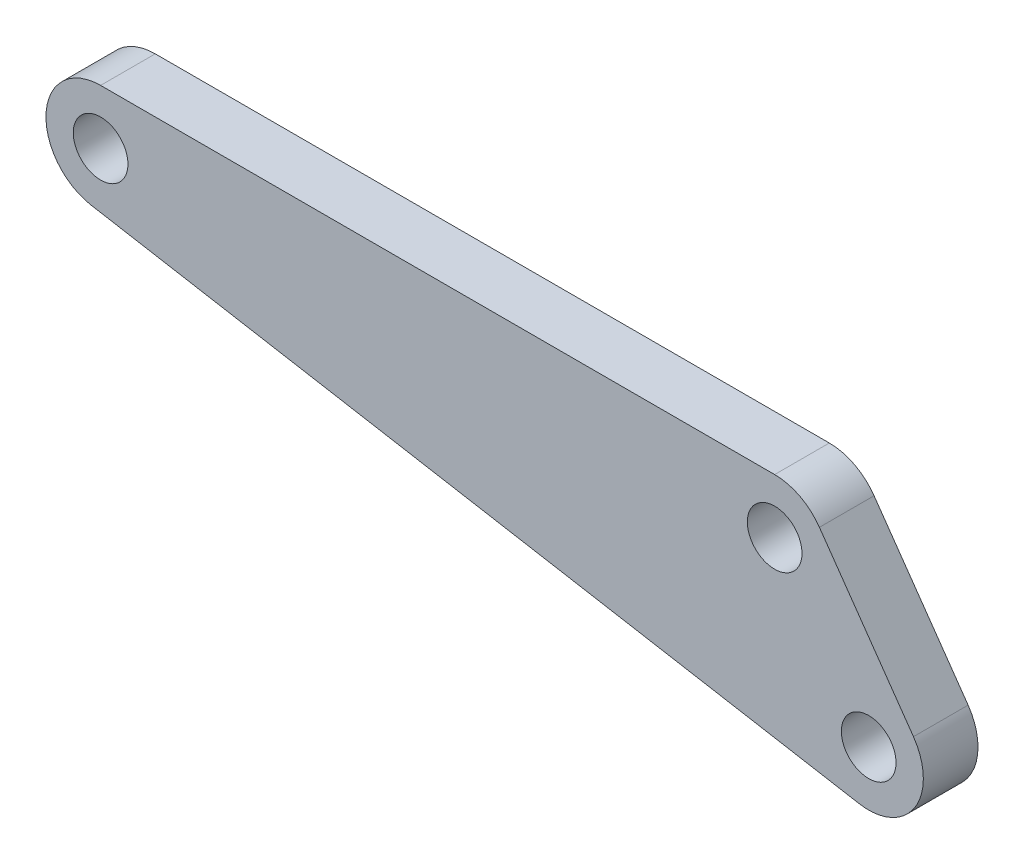
SolidWorks part; units mm, degrees
ref_plane "Front Plane" through (0, 0, 0) normal (0, 0, 1) x (1, 0, 0)
ref_plane "Top Plane" through (0, 0, 0) normal (0, 1, 0) x (1, 0, 0)
ref_plane "Right Plane" through (0, 0, 0) normal (1, 0, 0) x (0, 0, -1)
sketch "Sketch1" plane through (0, 0, 0) normal (0, 0, 1) x (1, 0, 0)
  line L0 (0, 0) -> (-37, 0)
  line L1 (0, 0) -> (5.1622, -7.3724)
  dimension "D1" = 37
  dimension "D2" = 9
  dimension "D3" = 125
sketch "Sketch2" plane through (0, 0, 0) normal (0, 0, 1) x (1, 0, 0)
  line L0 (-37, 3) -> (0, 3)
  line L1 (2.4575, 1.7207) -> (7.6196, -5.6516)
  line L2 (4.6455, -10.3275) -> (-37.5167, -2.9552)
  circle A0 centre (-37, 0) radius 1.5
  arc A1 (-37, 3) -> (-37.5167, -2.9552) centre (-37, 0) ccw
  circle A2 centre (0, 0) radius 1.5
  arc A3 (2.4575, 1.7207) -> (0, 3) centre (0, 0) ccw
  circle A4 centre (5.1622, -7.3724) radius 1.5
  arc A5 (4.6455, -10.3275) -> (7.6196, -5.6516) centre (5.1622, -7.3724) ccw
  dimension "D1" = 3
  dimension "D2" = 6
  dimension "D3" = 3
  dimension "D4" = 6
  dimension "D5" = 3
  dimension "D6" = 6
extrude "Boss-Extrude1" add sketch "Sketch2" along normal blind 3
